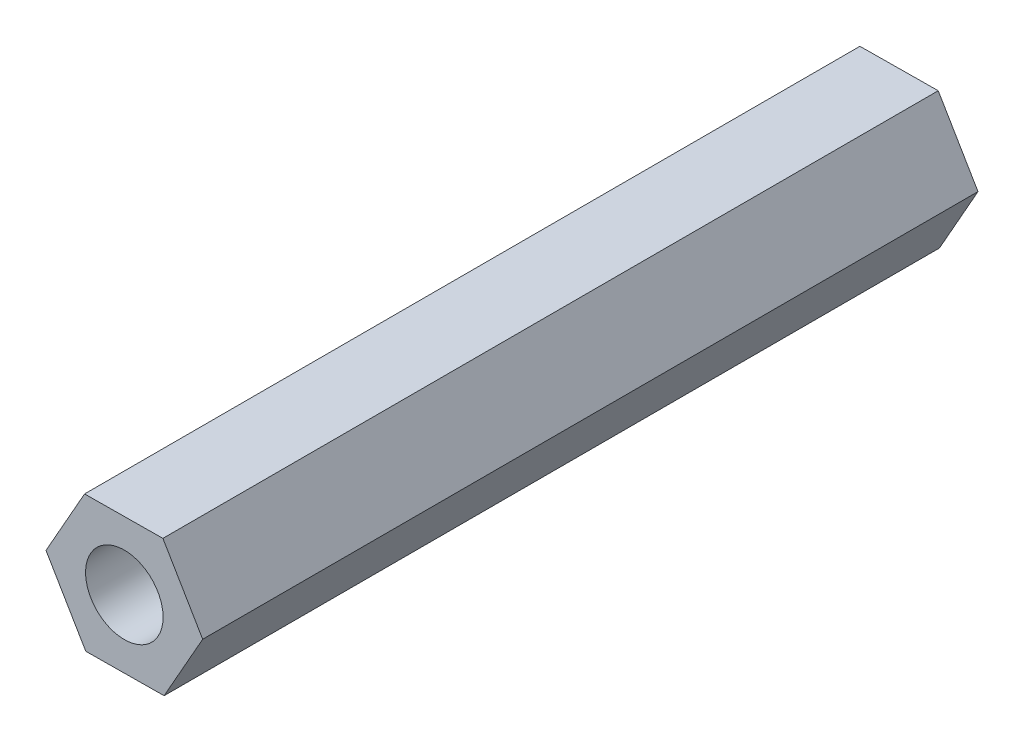
SolidWorks part; units mm, degrees
ref_plane "前视基准面" through (0, 0, 0) normal (0, 0, 1) x (1, 0, 0)
ref_plane "上视基准面" through (0, 0, 0) normal (0, 1, 0) x (1, 0, 0)
ref_plane "右视基准面" through (0, 0, 0) normal (1, 0, 0) x (0, 0, -1)
sketch "草图1" plane through (0, 0, 0) normal (0, 0, 1) x (1, 0, 0)
  line L1 (2.0515, -3.4821) -> (4.0413, 0.0356)
  line L2 (4.0413, 0.0356) -> (1.9898, 3.5177)
  line L3 (1.9898, 3.5177) -> (-2.0515, 3.4821)
  line L4 (-2.0515, 3.4821) -> (-4.0413, -0.0356)
  line L5 (-4.0413, -0.0356) -> (-1.9898, -3.5177)
  line L6 (-1.9898, -3.5177) -> (2.0515, -3.4821)
  circle A0 centre (0, 0) radius 3.5 construction
  circle A1 centre (0, 0) radius 2
extrude "凸台-拉伸1" add sketch "草图1" along normal blind 40
